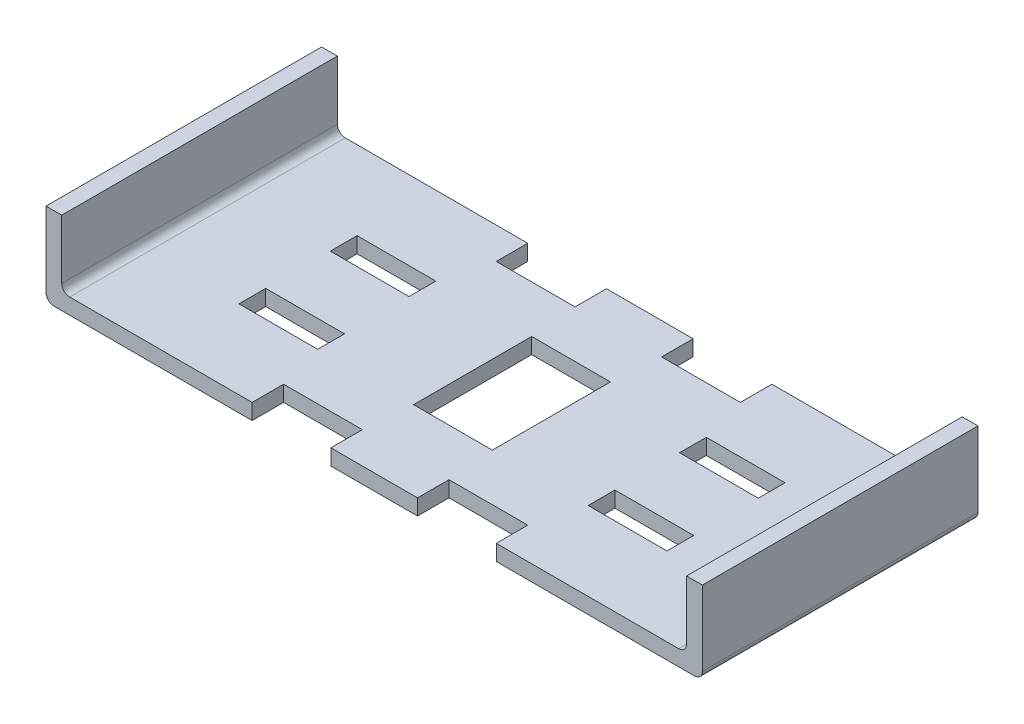
SolidWorks part; units mm, degrees
ref_plane "Front Plane" through (0, 0, 0) normal (0, 0, 1) x (1, 0, 0)
ref_plane "Top Plane" through (0, 0, 0) normal (0, 1, 0) x (1, 0, 0)
ref_plane "Right Plane" through (0, 0, 0) normal (1, 0, 0) x (0, 0, -1)
sketch "Sketch1" plane through (0, 0, 0) normal (0, 1, 0) x (1, 0, 0)
  line L1 (-83.35, 35) -> (83.35, 35)
  line L2 (-83.35, 35) -> (-83.35, -35)
  line L3 (-83.35, -35) -> (83.35, -35)
  line L4 (83.35, 35) -> (83.35, -35)
  line L5 (-83.35, 35) -> (83.35, -35) construction
  line L6 (-83.35, -35) -> (83.35, 35) construction
  point P0 (0, 0)
  dimension "D1" = 166.7
  dimension "D2" = 70
extrude "Boss-Extrude1" add sketch "Sketch1" along normal blind 4
sketch "Sketch2" plane through (0, 4, 0) normal (0, 1, 0) x (1, 0, 0)
  line L0 (83.35, 35) -> (-83.35, 35) construction
  line L1 (-83.35, -35) -> (-79.35, -35)
  line L2 (-83.35, -35) -> (-83.35, 35)
  line L3 (-83.35, 35) -> (-79.35, 35)
  line L4 (-79.35, -35) -> (-79.35, 35)
  line L5 (0, 0) -> (0, 53.5873) construction
  line L6 (79.35, -35) -> (79.35, 35)
  line L7 (83.35, 35) -> (79.35, 35)
  line L8 (83.35, -35) -> (83.35, 35)
  line L9 (83.35, -35) -> (79.35, -35)
  line M9 (83.35, -35) -> (83.35, 35)
  line M10 (83.35, 35) -> (-83.35, 35)
  line M12 (-83.35, -35) -> (83.35, -35)
  dimension "D1" = 4
extrude "Boss-Extrude2" add sketch "Sketch2" along normal blind 17 contours L6 M12 M9 M10 | L2 L1 L4 L3
sketch "Sketch3" plane through (0, 4, 0) normal (0, 1, 0) x (1, 0, 0)
  line L0 (-79.35, -35) -> (-79.35, 35) construction
  line L1 (-54.35, 15) -> (-34.35, 15)
  line L2 (-54.35, 15) -> (-54.35, 8.2)
  line L3 (-54.35, 8.2) -> (-34.35, 8.2)
  line L4 (-34.35, 15) -> (-34.35, 8.2)
  line L5 (79.35, 35) -> (-79.35, 35) construction
  line L6 (-54.35, -8.2) -> (-34.35, -8.2)
  line L7 (-54.35, -8.2) -> (-54.35, -15)
  line L8 (-54.35, -15) -> (-34.35, -15)
  line L9 (-34.35, -8.2) -> (-34.35, -15)
  line L10 (-79.35, -35) -> (79.35, -35) construction
  line L12 (34.35, -8.2) -> (34.35, -15)
  line L13 (54.35, -15) -> (34.35, -15)
  line L14 (54.35, -8.2) -> (54.35, -15)
  line L15 (54.35, -8.2) -> (34.35, -8.2)
  line L16 (34.35, 15) -> (34.35, 8.2)
  line L17 (54.35, 8.2) -> (34.35, 8.2)
  line L18 (54.35, 15) -> (54.35, 8.2)
  line L19 (54.35, 15) -> (34.35, 15)
  point P14 (-54.35, -11.6)
  dimension "D1" = 20
  dimension "D2" = 6.8
  dimension "D3" = 25
  dimension "D4" = 20
  dimension "D5" = 6.8
  dimension "D6" = 20
  dimension "D7" = 20
  dimension "D8" = 25
extrude "Cut-Extrude1" cut sketch "Sketch3" against normal through all contours L4 L1 L2 L3 | L9 L6 L7 L8 | L14 L15 L12 L13 | L16 L17 L18 L19
sketch "Sketch4" plane through (0, 0, 0) normal (0, -1, 0) x (1, 0, 0)
  line L1 (-10, 15) -> (10, 15)
  line L2 (-10, 15) -> (-10, -15)
  line L3 (-10, -15) -> (10, -15)
  line L4 (10, 15) -> (10, -15)
  line L5 (-10, 15) -> (10, -15) construction
  line L6 (-10, -15) -> (10, 15) construction
  point P0 (0, 0)
  dimension "D1" = 20
  dimension "D2" = 30
extrude "Cut-Extrude2" cut sketch "Sketch4" against normal through all
fillet "Fillet1" radius 2 4 edges at (-79.35, 4, 0) (79.35, 4, 0) (-83.35, 0, 0) (83.35, 0, 0)
sketch "Sketch5" plane through (0, 0, 0) normal (0, -1, 0) x (1, 0, 0)
  line L0 (-81.35, 35) -> (81.35, 35) construction
  line L1 (11, 35) -> (31, 35)
  line L2 (11, 35) -> (11, 27)
  line L3 (11, 27) -> (31, 27)
  line L4 (31, 35) -> (31, 27)
  line L5 (-11, -35) -> (-31, -35)
  line L7 (-31, 35) -> (-31, 27)
  line L8 (-11, 27) -> (-31, 27)
  line L9 (-11, 35) -> (-11, 27)
  line L10 (-11, 35) -> (-31, 35)
  line L11 (-11, -35) -> (-11, -27)
  line L12 (-11, -27) -> (-31, -27)
  line L13 (-31, -35) -> (-31, -27)
  line L14 (31, -35) -> (31, -27)
  line L15 (11, -27) -> (31, -27)
  line L16 (11, -35) -> (11, -27)
  line L17 (11, -35) -> (31, -35)
  line M30 (81.35, 35) -> (-81.35, 35)
  line M32 (-81.35, -35) -> (81.35, -35)
  dimension "D1" = 8
  dimension "D2" = 20
extrude "Cut-Extrude3" cut sketch "Sketch5" against normal through all contours L13 L11 L12 M32 | L9 L7 L8 M30 | L4 L2 L3 M30 | L14 L15 L16 L17
